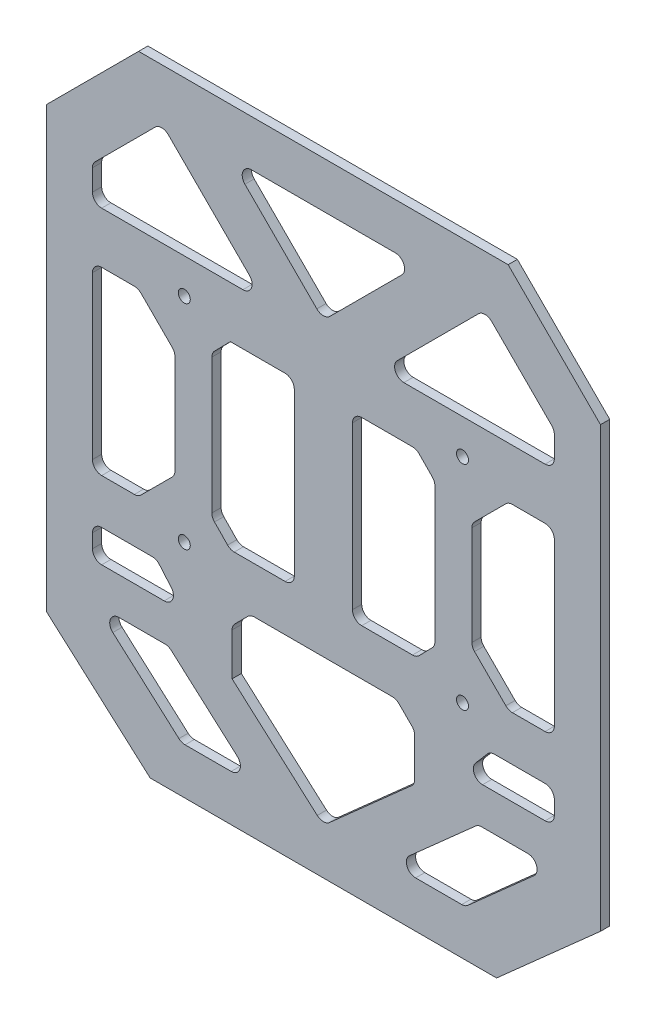
SolidWorks part; units mm, degrees
material "3.3549 (EN-AW 5182)"
ref_plane "Front Plane" through (0, 0, 0) normal (0, 0, 1) x (1, 0, 0)
ref_plane "Top Plane" through (0, 0, 0) normal (0, 1, 0) x (1, 0, 0)
ref_plane "Right Plane" through (0, 0, 0) normal (1, 0, 0) x (0, 0, -1)
sketch "Sketch1" plane through (0, 0, 0) normal (0, 0, 1) x (1, 0, 0)
  line L0 (0, 109.189) -> (0, -109.189) construction
  line L2 (-76.2, 60.325) -> (-76.2, -60.325)
  line L3 (-76.2, -60.325) -> (76.2, -60.325)
  line L4 (76.2, 60.325) -> (76.2, -60.325)
  line L5 (-76.2, 60.325) -> (76.2, -60.325) construction
  line L6 (-76.2, -60.325) -> (76.2, 60.325) construction
  line L7 (-50.8, 85.725) -> (50.8, 85.725)
  line L8 (-50.8, 85.725) -> (-76.2, 60.325)
  line L9 (50.8, 85.725) -> (76.2, 60.325)
  point P0 (0, 0)
  point P9 (0, 0)
  point P12 (0, 85.725)
  dimension "D1" = 146.05
  dimension "D2" = 25.4
  dimension "D3" = 152.4
extrude "Boss-Extrude1" add sketch "Sketch1" along normal mid plane 2.54
sketch "Sketch2" plane through (0, 0, 1.27) normal (0, 0, 1) x (1, 0, 0)
  line L0 (-47.625, -85.725) -> (47.625, -85.725)
  line L3 (-47.625, -85.725) -> (-76.2, -60.325)
  line L4 (-76.2, -60.325) -> (76.2, -60.325)
  line L5 (76.2, -60.325) -> (47.625, -85.725)
  dimension "D1" = 28.575
  dimension "D2" = 28.575
extrude "Boss-Extrude2" add sketch "Sketch2" against normal up to surface (2.54 mm away) up to face at (0, 28.575, -1.27)
sketch "Sketch3" plane through (0, 0, 1.27) normal (0, 0, 1) x (1, 0, 0)
  line L0 (0, 99.2674) -> (0, -99.2674) construction
  line L2 (47.625, -85.725) -> (76.2, -60.325) construction
  line L3 (-47.625, -85.725) -> (47.625, -85.725) construction
  line L5 (-76.2, -60.325) -> (-47.625, -85.725) construction
  line L6 (-25.1072, -50.8488) -> (-25.1072, -33.0688)
  line L7 (1.779, -20.6018) -> (-52.3639, -81.5126) construction
  line L8 (25.1072, -50.8488) -> (25.1072, -33.0688)
  line L10 (-25.1072, -33.0688) -> (25.1072, -33.0688)
  line L11 (-62.895, -51.7819) -> (-42.575, -51.7819)
  line L12 (-42.575, -51.7819) -> (-18.6765, -73.025)
  line L13 (-18.6765, -73.025) -> (-38.9965, -73.025)
  line L17 (-38.9965, -73.025) -> (-62.895, -51.7819)
  line L21 (-25.913, 73.025) -> (25.913, 73.025)
  line L23 (-25.1072, -50.8488) -> (0, -73.1663)
  line L24 (0, -73.1663) -> (25.1072, -50.8488)
  line L25 (-25.913, 73.025) -> (0, 47.112)
  line L26 (0, 47.112) -> (25.913, 73.025)
  line L27 (18.6765, -73.025) -> (38.9965, -73.025)
  line L28 (-44.45, 71.755) -> (-63.5, 52.705)
  line L29 (-63.5, 52.705) -> (-63.5, 43.302)
  line L30 (-44.45, 71.755) -> (-15.997, 43.302)
  line L31 (-15.997, 43.302) -> (-63.5, 43.302)
  line L32 (42.575, -51.7819) -> (18.6765, -73.025)
  line L33 (62.895, -51.7819) -> (42.575, -51.7819)
  line L34 (38.9965, -73.025) -> (62.895, -51.7819)
  line L35 (44.45, 71.755) -> (63.5, 52.705)
  line L36 (44.45, 71.755) -> (15.997, 43.302)
  line L37 (15.997, 43.302) -> (63.5, 43.302)
  line L38 (63.5, 52.705) -> (63.5, 43.302)
  line L39 (-7.9985, 29.21) -> (-63.5, 29.21)
  line L40 (63.5, 29.21) -> (63.5, -20.3688)
  line L41 (7.9985, 29.21) -> (63.5, 29.21)
  line L42 (7.9985, 29.21) -> (7.9985, -20.3688)
  line L43 (63.5, -20.3688) -> (7.9985, -20.3688)
  line L44 (-7.9985, 29.21) -> (-7.9985, -20.3688)
  line L45 (-63.5, 29.21) -> (-63.5, -20.3688)
  line L46 (-63.5, -20.3688) -> (-7.9985, -20.3688)
  point P4 (0, 0)
  point P27 (0, 73.025)
  dimension "D1" = 138.366
  dimension "D2" = 52.6562
  dimension "D3" = 17.78
  dimension "D5" = 90
  dimension "D6" = 20.32
  dimension "D8" = 12.7
extrude "Cut-Extrude1" cut sketch "Sketch3" against normal blind 2.54
sketch "Sketch4" plane through (0, 0, 1.27) normal (0, 0, 1) x (1, 0, 0)
  line L0 (30.6666, 29.21) -> (40.8266, 29.21)
  line L1 (63.5, 29.21) -> (7.9985, 29.21) construction
  line L2 (40.8266, 29.21) -> (40.8266, -20.3688)
  line L3 (7.9985, -20.3688) -> (63.5, -20.3688) construction
  line L4 (30.6666, 29.21) -> (30.6666, -20.3688)
  line L5 (30.6666, -20.3688) -> (40.8266, -20.3688)
  line L6 (0, 90.4262) -> (0, -90.4262) construction
  line L7 (30.6666, 29.21) -> (25.5866, 29.21)
  line L8 (25.5866, 29.21) -> (30.6666, 24.0171)
  line L9 (30.6666, 24.0171) -> (30.6666, 29.21)
  line L10 (-30.6666, 29.21) -> (-30.6666, -20.3688)
  line L11 (-30.6666, 29.21) -> (-40.8266, 29.21)
  line L12 (40.8266, 29.21) -> (48.3743, 29.21)
  line L13 (48.3743, 29.21) -> (40.8266, 21.6623)
  line L14 (40.8266, 21.6623) -> (40.8266, 29.21)
  line L15 (30.6666, -15.1759) -> (30.6666, -20.3688)
  line L16 (25.5866, -20.3688) -> (30.6666, -15.1759)
  line L17 (30.6666, -20.3688) -> (25.5866, -20.3688)
  line L18 (40.8266, -12.8211) -> (40.8266, -20.3688)
  line L19 (48.3743, -20.3688) -> (40.8266, -12.8211)
  line L20 (40.8266, -20.3688) -> (48.3743, -20.3688)
  line L21 (-40.8266, 29.21) -> (-40.8266, -20.3688)
  line L22 (-30.6666, -20.3688) -> (-40.8266, -20.3688)
  line L23 (-40.8266, -12.8211) -> (-40.8266, -20.3688)
  line L24 (-48.3743, -20.3688) -> (-40.8266, -12.8211)
  line L25 (-40.8266, -20.3688) -> (-48.3743, -20.3688)
  line L26 (-30.6666, -15.1759) -> (-30.6666, -20.3688)
  line L27 (-25.5866, -20.3688) -> (-30.6666, -15.1759)
  line L28 (-30.6666, -20.3688) -> (-25.5866, -20.3688)
  line L29 (-30.6666, 24.0171) -> (-30.6666, 29.21)
  line L30 (-25.5866, 29.21) -> (-30.6666, 24.0171)
  line L31 (-30.6666, 29.21) -> (-25.5866, 29.21)
  line L32 (-40.8266, 21.6623) -> (-40.8266, 29.21)
  line L33 (-48.3743, 29.21) -> (-40.8266, 21.6623)
  line L34 (-40.8266, 29.21) -> (-48.3743, 29.21)
  point P13 (0, 0)
extrude "Boss-Extrude3" add sketch "Sketch4" against normal up to surface (2.54 mm away) contours L34 L33 L32 | L10 L22 L21 L11 | L31 L30 L29 | L28 L27 L26 | L25 L24 L23 | L5 L2 L0 L4 | L20 L19 L18 | L17 L16 L15 | L12 L13 L14 | L7 L8 L9
sketch "Sketch5" plane through (0, 0, 1.27) normal (0, 0, 1) x (1, 0, 0)
  line L0 (-40.8266, 21.6623) -> (-40.8266, 19.1223)
  line L1 (-40.8266, 21.6623) -> (-40.8266, -12.8211) construction
  line L2 (-48.3743, 29.21) -> (-50.9143, 29.21)
  line L3 (-48.3743, 29.21) -> (-63.5, 29.21) construction
  line L4 (-50.9143, 29.21) -> (-40.8266, 19.1223)
  line L5 (-48.3743, 29.21) -> (-40.8266, 21.6623)
  line L6 (0, 106.3434) -> (0, -106.3434) construction
  line L7 (-7.9985, 4.4206) -> (-86.1981, 4.4206) construction
  line L8 (-7.9985, -20.3688) -> (-7.9985, 29.21) construction
  line L9 (-48.3743, -20.3688) -> (-50.9143, -20.3688)
  line L10 (-50.9143, -20.3688) -> (-40.8266, -10.2811)
  line L11 (-40.8266, -12.8211) -> (-40.8266, -10.2811)
  line L12 (-48.3743, -20.3688) -> (-40.8266, -12.8211)
  line L13 (48.3743, -20.3688) -> (40.8266, -12.8211)
  line L14 (40.8266, -12.8211) -> (40.8266, -10.2811)
  line L15 (50.9143, -20.3688) -> (40.8266, -10.2811)
  line L16 (48.3743, -20.3688) -> (50.9143, -20.3688)
  line L17 (48.3743, 29.21) -> (50.9143, 29.21)
  line L18 (50.9143, 29.21) -> (40.8266, 19.1223)
  line L19 (40.8266, 21.6623) -> (40.8266, 19.1223)
  line L20 (48.3743, 29.21) -> (40.8266, 21.6623)
  point P14 (0, 0)
  point P18 (0, 0)
extrude "Boss-Extrude4" add sketch "Sketch5" against normal up to surface (2.54 mm away) contours L5 L0 L4 L2 | L9 L10 L11 L12 | L17 L18 L19 L20 | L13 L14 L15 L16
sketch "Sketch6" plane through (0, 0, 1.27) normal (0, 0, 1) x (1, 0, 0)
  line L0 (0, 0) -> (0, 91.2749) construction
  line L1 (40.8266, 4.4206) -> (96.9821, 4.4206) construction
  line L2 (50.9143, -20.3688) -> (40.8266, -20.3688) construction
  line L4 (40.8266, 19.1223) -> (40.8266, -10.2811) construction
  line L5 (45.8704, -41.6219) -> (63.5, -41.6219)
  line L6 (63.5, -41.6219) -> (63.5, -32.7319)
  line L7 (63.5, -32.7319) -> (45.8704, -32.7319)
  line L8 (38.2504, -41.6219) -> (45.8704, -41.6219)
  line L9 (45.8704, -32.7319) -> (38.2504, -41.6219)
  line L10 (-63.5, -41.6219) -> (-63.5, -32.7319)
  line L11 (-45.8704, -41.6219) -> (-63.5, -41.6219)
  line L12 (-38.2504, -41.6219) -> (-45.8704, -41.6219)
  line L13 (-45.8704, -32.7319) -> (-38.2504, -41.6219)
  line L14 (-63.5, -32.7319) -> (-45.8704, -32.7319)
  circle A0 centre (38.2504, 33.7178) radius 1.65
  circle A1 centre (38.2504, -24.8766) radius 1.65
  circle A2 centre (-38.2504, -24.8766) radius 1.65
  circle A3 centre (-38.2504, 33.7178) radius 1.65
  point P10 (38.2504, 29.21)
  dimension "D1" = 3.3
extrude "Cut-Extrude2" cut sketch "Sketch6" against normal blind 2.54
chamfer "Chamfer1" distance 5.08 angle 45 2 edges at (25.1072, -33.0688, 0) (-25.1072, -33.0688, 0)
fillet "Fillet1" radius 2.54 22 edges at (-63.5, -41.6219, 0) (-63.5, -32.7319, 0) (-45.8704, -32.7319, 0) (-38.2504, -41.6219, 0) (63.5, -41.6219, 0) (63.5, -32.7319, 0) (45.8704, -32.7319, 0) (38.2504, -41.6219, 0) (38.9965, -73.025, 0) (42.575, -51.7819, 0) (62.895, -51.7819, 0) (18.6765, -73.025, 0) (-38.9965, -73.025, 0) (-62.895, -51.7819, 0) (-42.575, -51.7819, 0) (-18.6765, -73.025, 0) (0, -73.1663, 0) (25.1072, -50.8488, 0) (25.1072, -38.1488, 0) (20.0272, -33.0688, 0) (-25.1072, -38.1488, 0) (-20.0272, -33.0688, 0)
fillet "Fillet2" radius 2.54 34 edges at (-50.9143, -20.3688, 0) (-63.5, -20.3688, 0) (-63.5, 29.21, 0) (-50.9143, 29.21, 0) (-40.8266, -10.2811, 0) (-40.8266, 19.1223, 0) (-7.9985, -20.3688, 0) (-7.9985, 29.21, 0) (-30.6666, 24.0171, 0) (-25.5866, -20.3688, 0) (-30.6666, -15.1759, 0) (63.5, -20.3688, 0) (63.5, 29.21, 0) (50.9143, 29.21, 0) (40.8266, 19.1223, 0) (50.9143, -20.3688, 0) (40.8266, -10.2811, 0) (30.6666, -15.1759, 0) (25.5866, -20.3688, 0) (7.9985, -20.3688, 0) (30.6666, 24.0171, 0) (25.5866, 29.21, 0) (7.9985, 29.21, 0) (-63.5, 43.302, 0) (-63.5, 52.705, 0) (-44.45, 71.755, 0) (-15.997, 43.302, 0) (63.5, 52.705, 0) (63.5, 43.302, 0) (15.997, 43.302, 0) (44.45, 71.755, 0) (0, 47.112, 0) (-25.913, 73.025, 0) (25.913, 73.025, 0)
